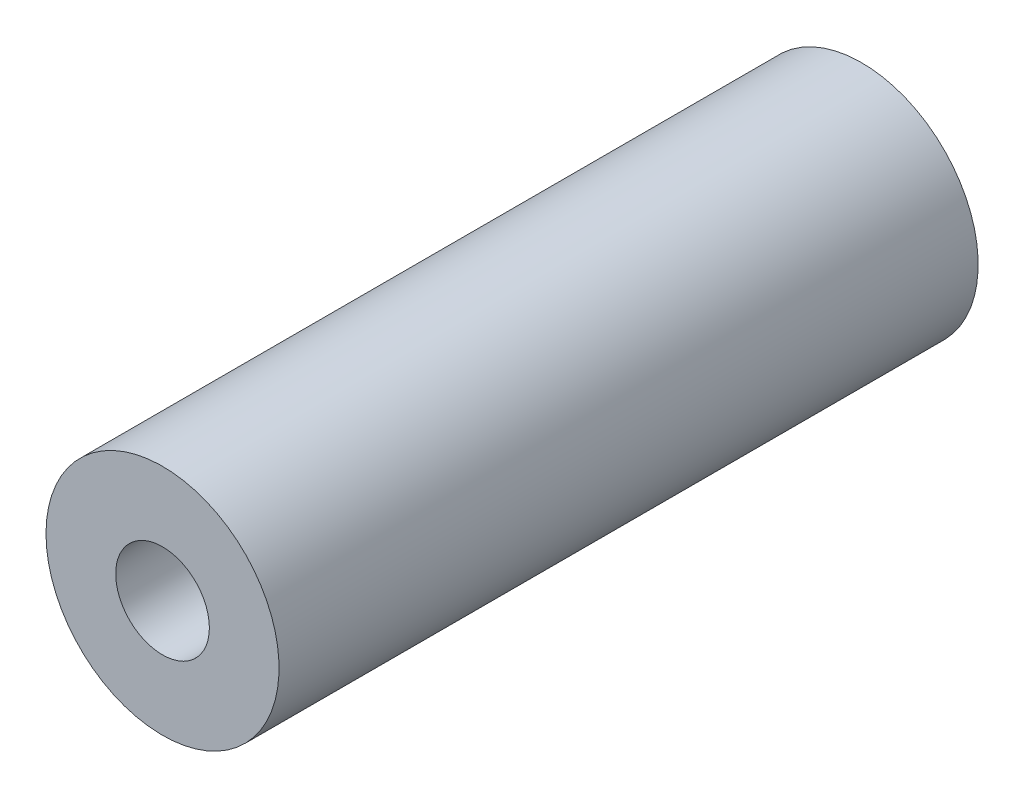
SolidWorks part; units mm, degrees
ref_plane "Front Plane" through (0, 0, 0) normal (0, 0, 1) x (1, 0, 0)
ref_plane "Top Plane" through (0, 0, 0) normal (0, 1, 0) x (1, 0, 0)
ref_plane "Right Plane" through (0, 0, 0) normal (1, 0, 0) x (0, 0, -1)
sketch "Sketch1" plane through (0, 0, 0) normal (0, 0, 1) x (1, 0, 0)
  circle A0 centre (0, 0) radius 6.35
  dimension "D1" = 12.7
extrude "Handle Base" add sketch "Sketch1" along normal blind 38.1
sketch "Sketch2" plane through (0, 0, 38.1) normal (0, 0, 1) x (1, 0, 0)
  circle A0 centre (0, 0) radius 2.5527
  dimension "D1" = 5.1054
hole_wizard "1/4-20 Tapped Hole1" positions "3DSketch1" profile "Sketch3" tap size "1/4-20" standard "ANSI Inch"
sketch3d "3DSketch1"
  point P0 (0, 0, 38.1)
sketch "Sketch3" plane through (0, 0, 38.1) normal (1, 0, 0) x (0, -1, 0)
  line L0 (0, 0) -> (0, 24.13)
  line L1 (0, 24.13) -> (2.5527, 22.5962)
  line L2 (2.5527, 22.5962) -> (2.5527, 0)
  line L5 (2.5527, 0) -> (0, 0)
  line L10 (0, 24.13) -> (-2.5527, 22.5962) construction
  line L11 (0, -6.35) -> (0, 107.95) construction
  dimension "Tap Drill Dia." = 5.1054
  dimension "Tap Drill Depth" = 24.13
  dimension "Drill Angle" = 118
cosmetic thread "Hole Thread1" parameters "D1"=19.05, "D2"=6.35
extrude "Cut-Extrude1" cut sketch "Sketch2" against normal through all contours A0
